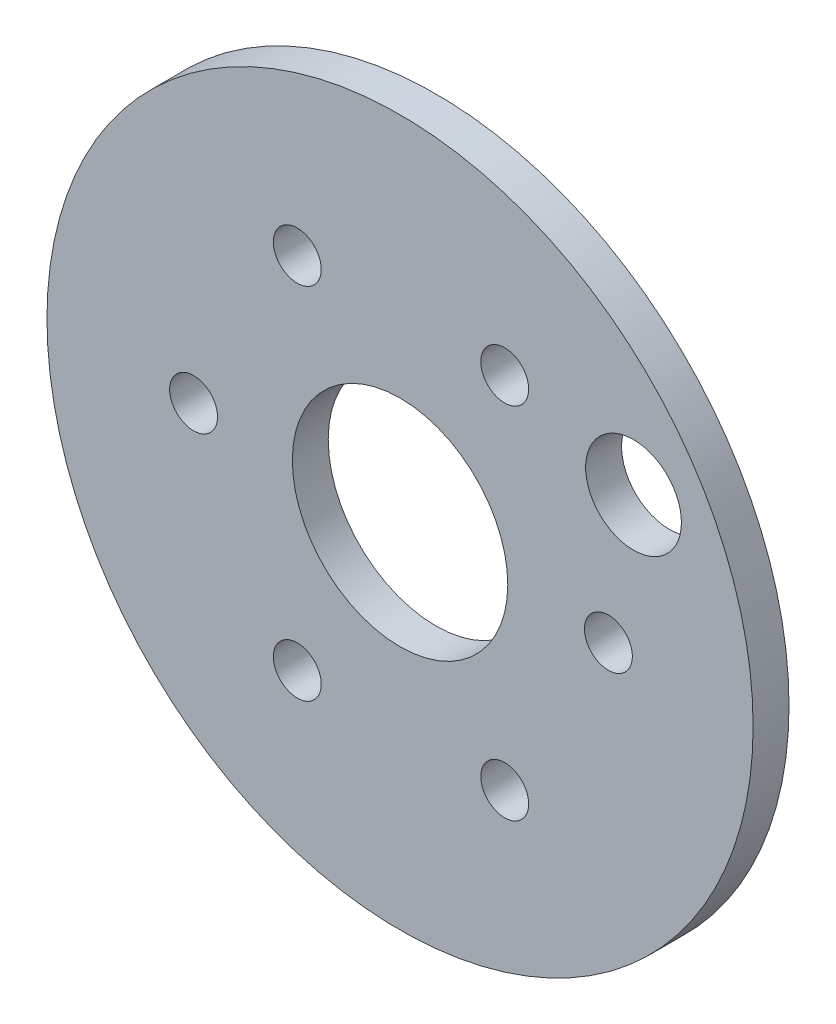
SolidWorks part; units mm, degrees
ref_plane "前视基准面" through (0, 0, 0) normal (0, 0, 1) x (1, 0, 0)
ref_plane "上视基准面" through (0, 0, 0) normal (0, 1, 0) x (1, 0, 0)
ref_plane "右视基准面" through (0, 0, 0) normal (1, 0, 0) x (0, 0, -1)
sketch "草图2" plane through (0, 0, 0) normal (0, 0, 1) x (1, 0, 0)
  circle A0 centre (0, 0) radius 29.5
  dimension "D1" = 59
extrude "凸台-拉伸1" add sketch "草图2" along normal blind 3
sketch "草图3" plane through (0, 0, 3) normal (0, 0, 1) x (1, 0, 0)
  circle A0 centre (0, 0) radius 17.25 construction
  circle A1 centre (-17.25, 0) radius 2
  dimension "D1" = 34.5
  dimension "D2" = 4
extrude "切除-拉伸1" cut sketch "草图3" against normal blind 3 contours A1
pattern_circular "阵列(圆周)1" count 6 every 60 about axis through (0.0797, 0, 0) along (0, 0, 1) of "切除-拉伸1"
sketch "草图4" plane through (0, 0, 3) normal (0, 0, 1) x (1, 0, 0)
  circle A0 centre (0, 0) radius 9
  dimension "D1" = 18
extrude "切除-拉伸2" cut sketch "草图4" against normal blind 3
sketch "草图5" plane through (0, 0, 3) normal (0, 0, 1) x (1, 0, 0)
  circle A0 centre (19.5072, 11.7415) radius 4
  dimension "D1" = 8
extrude "切除-拉伸3" cut sketch "草图5" against normal blind 10
